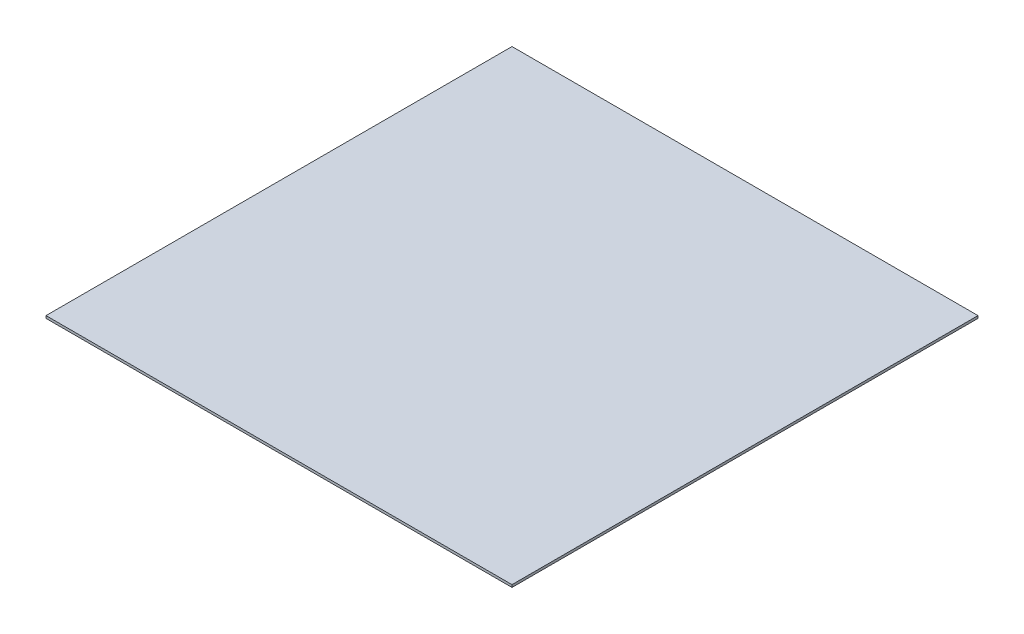
SolidWorks part; units mm, degrees
material "Silicon Rubber"
ref_plane "Front Plane" through (0, 0, 0) normal (0, 0, 1) x (1, 0, 0)
ref_plane "Top Plane" through (0, 0, 0) normal (0, 1, 0) x (1, 0, 0)
ref_plane "Right Plane" through (0, 0, 0) normal (1, 0, 0) x (0, 0, -1)
sketch "Sketch1" plane through (0, 0, 0) normal (0, 1, 0) x (1, 0, 0)
  line L1 (144.78, -144.78) -> (-144.78, -144.78)
  line L2 (144.78, -144.78) -> (144.78, 144.78)
  line L3 (144.78, 144.78) -> (-144.78, 144.78)
  line L4 (-144.78, -144.78) -> (-144.78, 144.78)
  line L5 (144.78, -144.78) -> (-144.78, 144.78) construction
  line L6 (144.78, 144.78) -> (-144.78, -144.78) construction
  point P0 (0, 0)
  dimension "D1" = 289.56
extrude "Boss-Extrude1" add sketch "Sketch1" along normal blind 1.524
